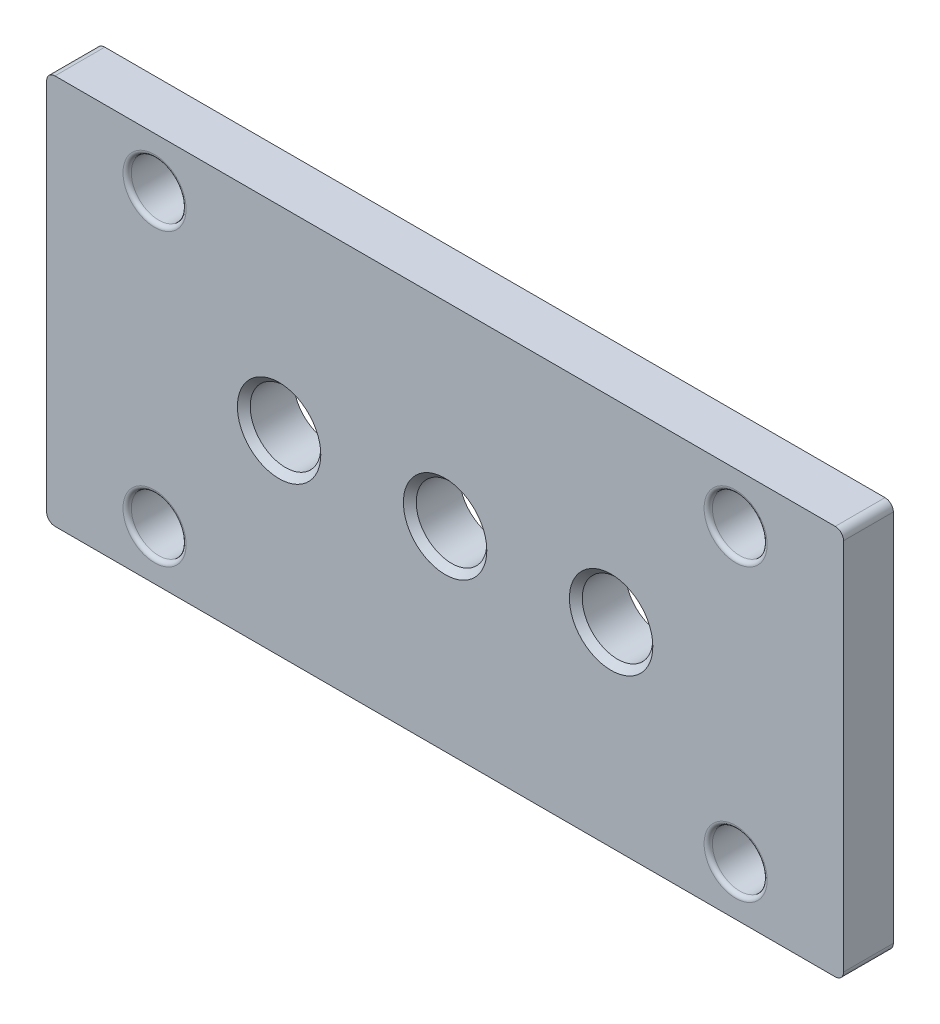
SolidWorks part; units mm, degrees
ref_plane "前视基准面" through (0, 0, 0) normal (0, 0, 1) x (1, 0, 0)
ref_plane "上视基准面" through (0, 0, 0) normal (0, 1, 0) x (1, 0, 0)
ref_plane "右视基准面" through (0, 0, 0) normal (1, 0, 0) x (0, 0, -1)
other "Configuration Table"
sketch "草图1" plane through (0, 0, 0) normal (0, 0, 1) x (1, 0, 0)
  line L0 (0, 0) -> (96, 0)
  line L1 (96, 0) -> (96, -47)
  line L2 (96, -47) -> (0, -47)
  line L3 (0, -47) -> (0, 0)
  dimension "D1" = 96
  dimension "D2" = 47
extrude "凸台-拉伸1" add sketch "草图1" along normal blind 6
sketch "草图2" plane through (0, 0, 6) normal (0, 0, 1) x (1, 0, 0)
  line L0 (96, -23.5) -> (0, -23.5)
  line L1 (96, -47) -> (96, 0) construction
  line L2 (0, 0) -> (0, -47) construction
  line L3 (48, 0) -> (48, -47)
  line L4 (96, 0) -> (0, 0) construction
  line L5 (0, -47) -> (96, -47) construction
  line L6 (48, -23.5) -> (48, -12)
  circle A0 centre (83, -6) radius 3.3
  circle A1 centre (83, -41) radius 3.3
  circle A2 centre (13, -41) radius 3.3
  circle A3 centre (13, -6) radius 3.3
  dimension "D1" = 35
  dimension "D2" = 17.5
fillet "圆角1" radius 1 4 edges at (96, -47, 3) (0, -47, 3) (0, 0, 3) (96, 0, 3)
sketch "草图8" plane through (0, 0, 6) normal (0, 0, 1) x (1, 0, 0)
  line L5 (48, -47) -> (48, 0)
  line L6 (1, -47) -> (95, -47) construction
  line L7 (95, 0) -> (1, 0) construction
  line L8 (96, -23.5) -> (0, -23.5)
  line L9 (96, -46) -> (96, -1) construction
  line L10 (0, -1) -> (0, -46) construction
  line L11 (48, -23.5) -> (78, -23.5)
  line L12 (48, -23.5) -> (18, -23.5)
  circle A1 centre (48, -23.5) radius 3.7667
  circle A3 centre (68, -23.5) radius 3.2586
  circle A4 centre (28, -23.5) radius 3.1199
  dimension "D3" = 20
  dimension "D2" = 60
  dimension "D4" = 20
hole_wizard "M10 螺纹孔1" positions "草图9" profile "草图10" tap size "M10" standard "GB" end condition through all
sketch "草图9" plane through (0, 0, 6) normal (0, 0, 1) x (1, 0, 0)
  line L0 (96, -23.5) -> (0, -23.5) construction
  point P0 (28, -23.5)
  point P3 (48, -23.5)
  point P7 (68, -23.5)
sketch "草图10" plane through (28, -23.5, 6) normal (1, 0, 0) x (0, -1, 0)
  line L0 (0, 0) -> (0, 6)
  line L1 (0, 6) -> (4.25, 6)
  line L2 (4.25, 6) -> (4.25, 0.775)
  line L3 (4.25, 0.775) -> (5.025, 0)
  line L5 (5.025, 0) -> (0, 0)
  line L6 (-4.25, 0.775) -> (-5.025, 0) construction
  line L11 (0, -6.35) -> (0, 107.95) construction
  dimension "通孔螺纹孔钻头直径" = 8.5
  dimension "通孔螺纹孔钻头深度" = 6
  dimension "近端锥形沉头孔直径" = 10.05
  dimension "近端锥形沉头孔角度" = 90
cosmetic thread "孔螺蚊线1" parameters "D2"=10
cosmetic thread "孔螺蚊线2" parameters "D2"=10
cosmetic thread "孔螺蚊线3" parameters "D2"=10
extrude "切除-拉伸1" cut sketch "草图2" against normal blind 10 contours A0 | A1 | A2 | A3
fillet "圆角2" radius 0.5 4 edges at (16.3, -41, 6) (86.3, -41, 6) (86.3, -6, 6) (9.7, -6, 6)
